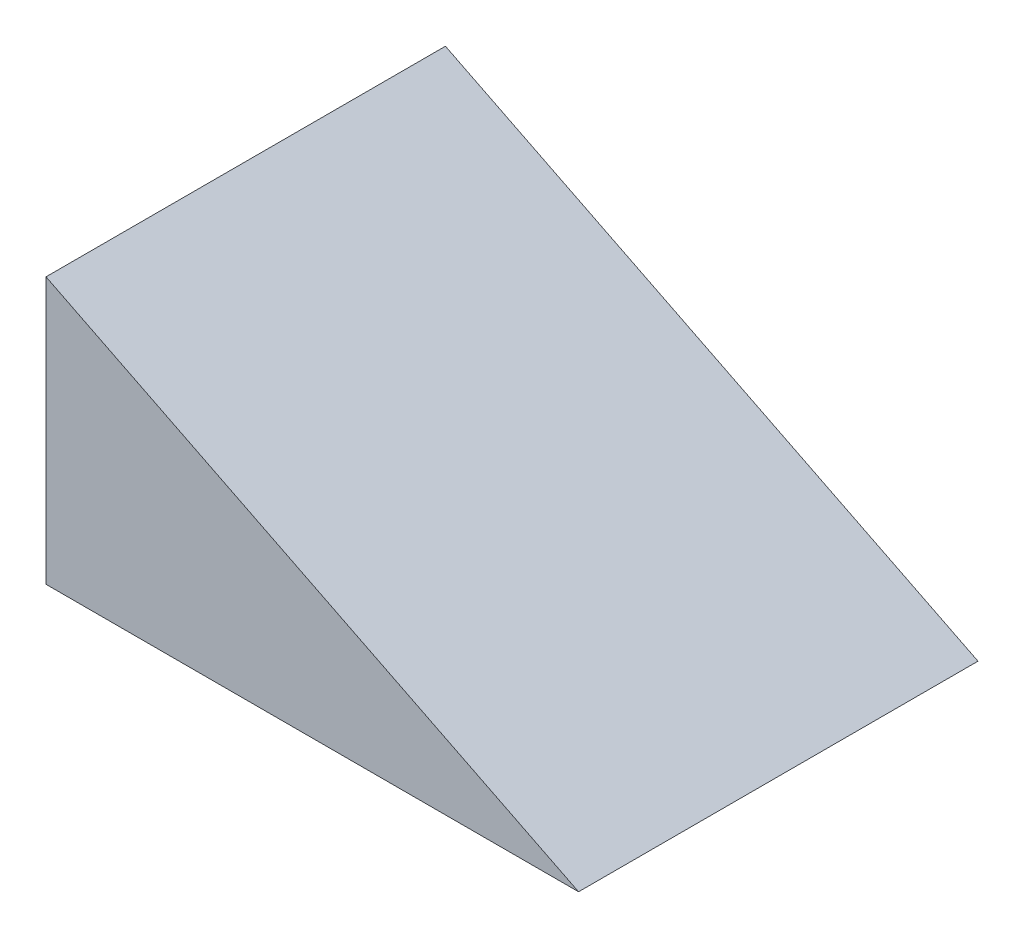
SolidWorks part; units mm, degrees
ref_plane "Front" through (0, 0, 0) normal (0, 0, 1) x (1, 0, 0)
ref_plane "Top" through (0, 0, 0) normal (0, 1, 0) x (1, 0, 0)
ref_plane "Right" through (0, 0, 0) normal (1, 0, 0) x (0, 0, -1)
sketch "Sketch1" plane through (0, 0, 0) normal (0, 0, 1) x (1, 0, 0)
  line L0 (0, 0) -> (0, 25.4)
  line L1 (0, 25.4) -> (50.8, 0)
  line L2 (50.8, 0) -> (0, 0)
  dimension "D1" = 50.8
  dimension "D2" = 25.4
extrude "Boss-Extrude1" add sketch "Sketch1" against normal blind 38.1
